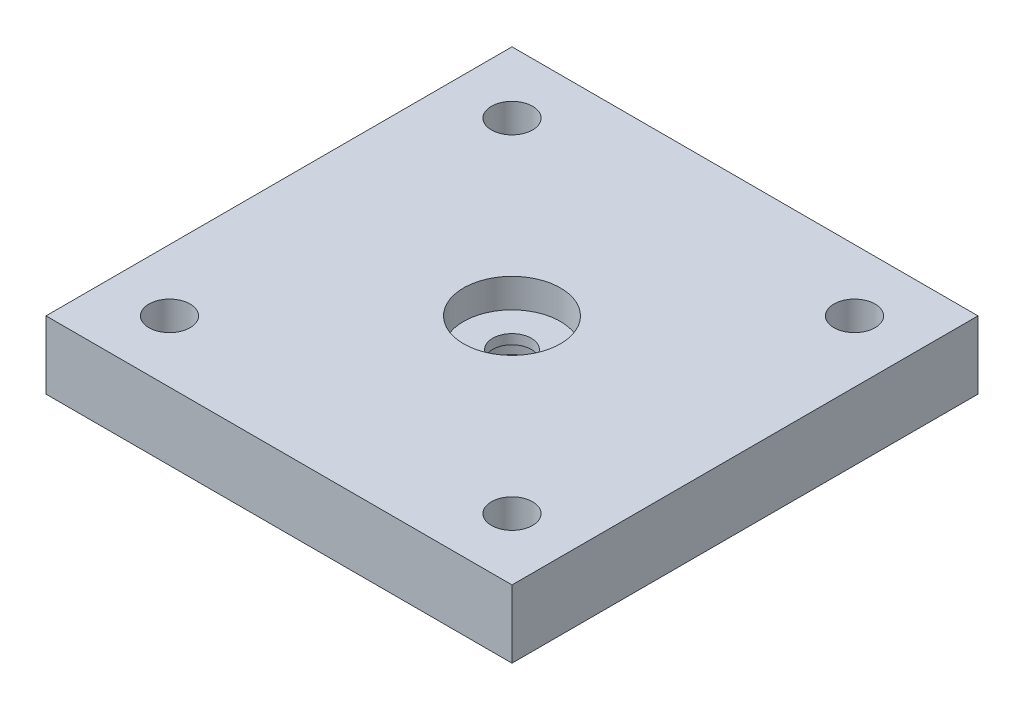
SolidWorks part; units mm, degrees
ref_plane "Front" through (0, 0, 0) normal (0, 0, 1) x (1, 0, 0)
ref_plane "Top" through (0, 0, 0) normal (0, 1, 0) x (1, 0, 0)
ref_plane "Right" through (0, 0, 0) normal (1, 0, 0) x (0, 0, -1)
sketch "Sketch1" plane through (0, 0, 0) normal (0, 1, 0) x (1, 0, 0)
  line L1 (-48.1053, 48.1053) -> (48.1053, 48.1053)
  line L2 (-48.1053, 48.1053) -> (-48.1053, -48.1053)
  line L3 (-48.1053, -48.1053) -> (48.1053, -48.1053)
  line L4 (48.1053, 48.1053) -> (48.1053, -48.1053)
  line L5 (-48.1053, 48.1053) -> (48.1053, -48.1053) construction
  line L6 (-48.1053, -48.1053) -> (48.1053, 48.1053) construction
  circle A0 centre (-35.3553, 35.3553) radius 4.25
  circle A1 centre (35.3553, 35.3553) radius 4.25
  circle A2 centre (35.3553, -35.3553) radius 4.25
  circle A3 centre (-35.3553, -35.3553) radius 4.25
  circle A4 centre (0, 0) radius 4
  point P0 (0, 0)
  point P17 (0, 0)
  dimension "D3" = 8.5
  dimension "D7" = 8
  dimension "D2" = 50
  dimension "D5" = 50
  dimension "D6" = 50
  dimension "D1" = 12.75
  dimension "D4" = 4
extrude "Boss-Extrude1" add sketch "Sketch1" along normal blind 14
sketch "Sketch2" plane through (0, 14, 0) normal (0, 1, 0) x (1, 0, 0)
  circle A0 centre (0, 0) radius 10
  dimension "D1" = 20
extrude "Cut-Extrude1" cut sketch "Sketch2" against normal blind 6
sketch "Sketch3" plane through (0, 0, 0) normal (0, -1, 0) x (1, 0, 0)
  circle A0 centre (0, 0) radius 10
  dimension "D1" = 20
extrude "Cut-Extrude2" cut sketch "Sketch3" against normal blind 6
equation "\"motor mount pattern diameter\"= 30mm"
equation "\"motor mount m6 screw hole diameter\"= 6.5mm"
equation "\"coupler shaft hole diameter\"= 20mm"
equation "\"motor mount m6 screw socket head diameter\"= 10.5mm"
equation "\"motor mount m6 screw socket head depth\"= 6mm"
equation "\"mount to housing m8 screw diameter\"= 8.5mm"
equation "\"motor to housing distance\"= 60mm"
equation "\"mount to housing m8 screw post radius\"= ( 3 * \"mount to housing m8 screw diameter\" ) / 2"
equation "\"mount to housing m8 pattern diameter\"= 100mm"
equation "\"plate thickness\"= \"motor mount m6 screw socket head depth\" + 6mm"
equation "\"D2@Sketch1\"=\"mount to housing m8 pattern diameter\"/2"
equation "\"D3@Sketch1\"=\"mount to housing m8 screw diameter\""
equation "\"D5@Sketch1\"=\"mount to housing m8 pattern diameter\"/2"
equation "\"D6@Sketch1\"=\"mount to housing m8 pattern diameter\"/2"
equation "\"D1@Sketch1\"=\"mount to housing m8 screw post radius\""
equation "\"adapter shaft smallest bore\"= 8mm"
equation "\"adapter shaft medium bore\"= 9mm"
equation "\"adapter shaft largest bore\"= 10mm"
equation "\"D7@Sketch1\"=\"adapter shaft smallest bore\""
equation "\"bearing hole depth\"= 6mm"
equation "\"seal hole depth\"= 6mm"
equation "\"bearing-seal lip thickness\"= 2mm"
equation "\"housing base thickness\"= \"bearing-seal lip thickness\" + \"seal hole depth\" + \"bearing hole depth\""
equation "\"D1@Boss-Extrude1\"=\"housing base thickness\""
equation "\"bearing diamater\"= 20mm"
equation "\"seal diameter\"= 20mm"
equation "\"D1@Sketch2\"=\"seal diameter\""
equation "\"D1@Cut-Extrude1\"=\"seal hole depth\""
equation "\"D1@Sketch3\"=\"bearing diamater\""
equation "\"D1@Cut-Extrude2\"=\"bearing hole depth\""
